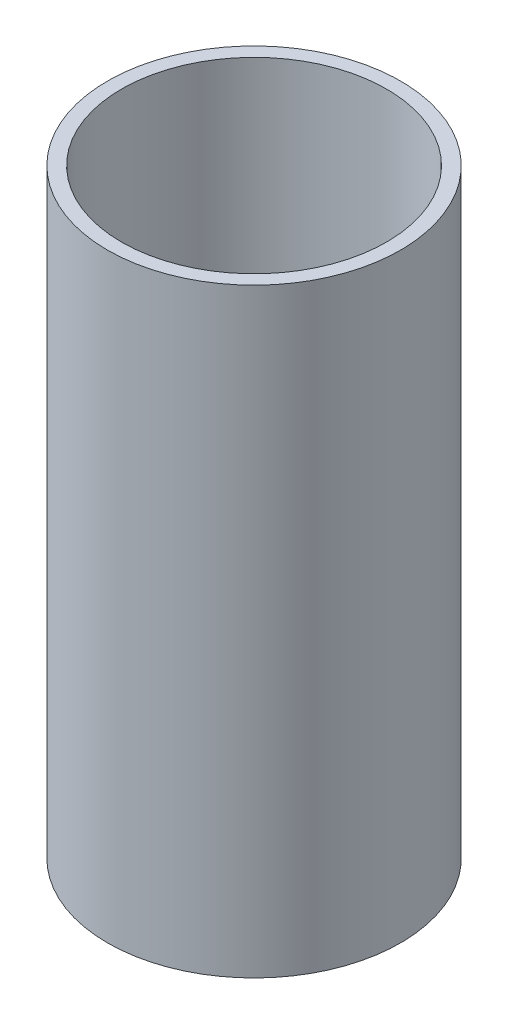
SolidWorks part; units mm, degrees
ref_plane "前基準面" through (0, 0, 0) normal (0, 0, 1) x (1, 0, 0)
ref_plane "上基準面" through (0, 0, 0) normal (0, 1, 0) x (1, 0, 0)
ref_plane "右基準面" through (0, 0, 0) normal (1, 0, 0) x (0, 0, -1)
sketch "草圖1" plane through (0, 0, 0) normal (0, 1, 0) x (1, 0, 0)
  circle A0 centre (0, 0) radius 10.5
  circle A1 centre (0, 0) radius 9.5
  dimension "D1" = 19
  dimension "D2" = 21
extrude "填料-伸長1" add sketch "草圖1" along normal blind 43
